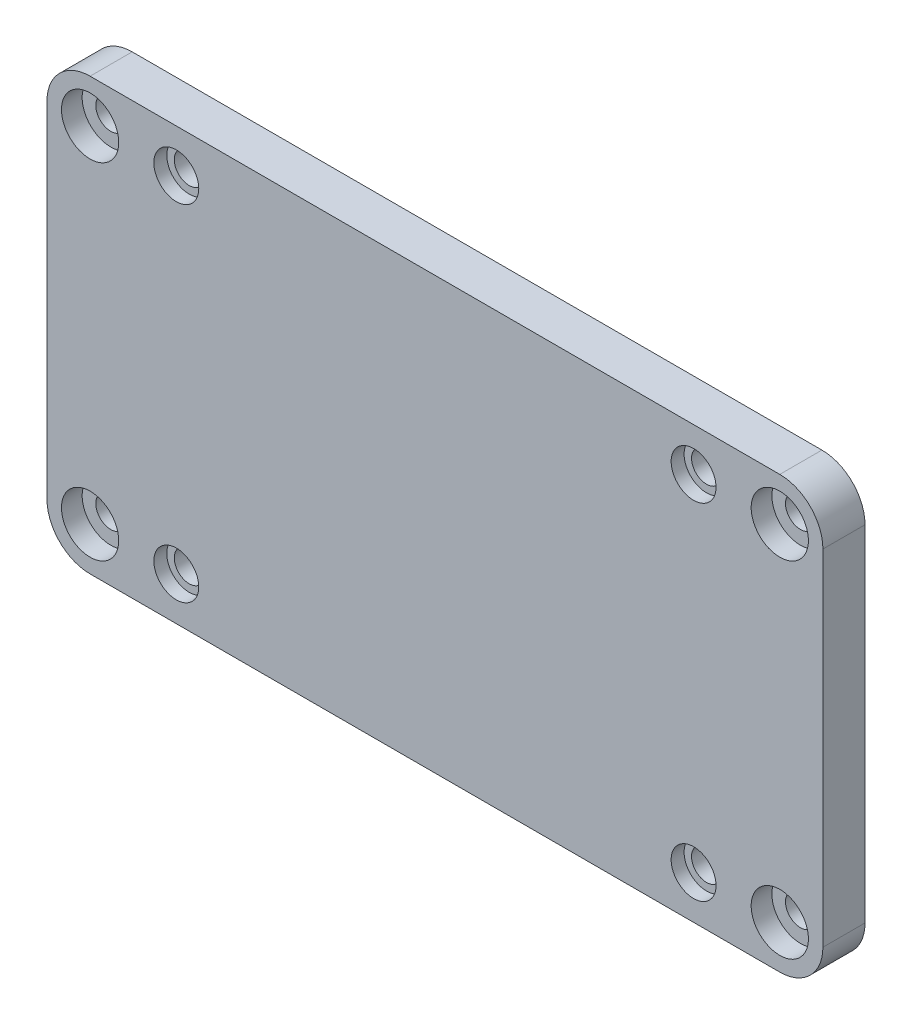
SolidWorks part; units mm, degrees
material "ABS"
ref_plane "Front Plane" through (0, 0, 0) normal (0, 0, 1) x (1, 0, 0)
ref_plane "Top Plane" through (0, 0, 0) normal (0, 1, 0) x (1, 0, 0)
ref_plane "Right Plane" through (0, 0, 0) normal (1, 0, 0) x (0, 0, -1)
sketch "Sketch1" plane through (0, 0, 0) normal (0, 0, 1) x (1, 0, 0)
  line L1 (-50.8, -31.75) -> (50.8, -31.75)
  line L2 (-57.15, -25.4) -> (-57.15, 25.4)
  line L3 (-50.8, 31.75) -> (50.8, 31.75)
  line L4 (57.15, -25.4) -> (57.15, 25.4)
  line L5 (-57.15, -31.75) -> (57.15, 31.75) construction
  line L6 (-57.15, 31.75) -> (57.15, -31.75) construction
  arc A0 (50.8, -31.75) -> (57.15, -25.4) centre (50.8, -25.4) ccw
  arc A1 (50.8, 31.75) -> (57.15, 25.4) centre (50.8, 25.4) cw
  arc A2 (-57.15, 25.4) -> (-50.8, 31.75) centre (-50.8, 25.4) cw
  arc A3 (-50.8, -31.75) -> (-57.15, -25.4) centre (-50.8, -25.4) cw
  circle A4 centre (-50.8, -25.4) radius 2.2098
  circle A5 centre (-50.8, 25.4) radius 2.2098
  circle A6 centre (50.8, 25.4) radius 2.2098
  circle A7 centre (50.8, -25.4) radius 2.2098
  point P0 (0, 0)
  dimension "D3" = 6.35
  dimension "D4" = 4.4196
  dimension "D1" = 114.3
  dimension "D2" = 63.5
extrude "Boss-Extrude1" add sketch "Sketch1" along normal blind 6.203
sketch "Sketch2" plane through (0, 0, 6.203) normal (0, 0, 1) x (1, 0, 0)
  circle A0 centre (-50.8, 25.4) radius 4.2164
  circle A1 centre (50.8, 25.4) radius 4.2164
  circle A2 centre (50.8, -25.4) radius 4.2164
  circle A3 centre (-50.8, -25.4) radius 4.2164
  dimension "D1" = 8.4328
extrude "Cut-Extrude1" cut sketch "Sketch2" against normal blind 3.048
sketch "Sketch3" plane through (0, 0, 6.203) normal (0, 0, 1) x (1, 0, 0)
  line L0 (-50.8, 25.4) -> (-38.1, 25.4) construction
  line L1 (0, -55) -> (0, 55) construction
  line L2 (55, 0) -> (-55, 0) construction
  circle A0 centre (-38.1, 25.4) radius 2.2098
  circle A1 centre (-50.8, 25.4) radius 2.2098 construction
  circle A2 centre (38.1, 25.4) radius 2.2098
  circle A3 centre (38.1, -25.4) radius 2.2098
  circle A4 centre (-38.1, -25.4) radius 2.2098
  point P4 (0, 0)
  dimension "D2" = 4.4196
  dimension "D1" = 12.7
extrude "Cut-Extrude2" cut sketch "Sketch3" against normal through all
sketch "Sketch4" plane through (0, 0, 6.203) normal (0, 0, 1) x (1, 0, 0)
  circle A0 centre (-38.1, 25.4) radius 3.307
  circle A1 centre (38.1, 25.4) radius 3.307
  circle A2 centre (38.1, -25.4) radius 3.307
  circle A3 centre (-38.1, -25.4) radius 3.307
  dimension "D1" = 6.614
extrude "Cut-Extrude3" cut sketch "Sketch4" against normal blind 1.907
equation "\"tolerance\"= 0.005"
equation "\"D1@Boss-Extrude1\"=4.55mm+1.78mm-\"tolerance\""
equation "\"D4@Sketch1\" = .164 + \"tolerance\" * 2"
equation "\"D1@Sketch2\"= .322 + \"tolerance\" * 2"
equation "\"D1@Cut-Extrude1\"= .115 + \"tolerance\""
equation "\"D2@Sketch3\"=0.164 + \"tolerance\" * 2"
equation "\"D1@Cut-Extrude3\"=1.78mm+\"tolerance\""
equation "\"D1@Sketch4\"=(3.18mm+\"tolerance\")*2"
